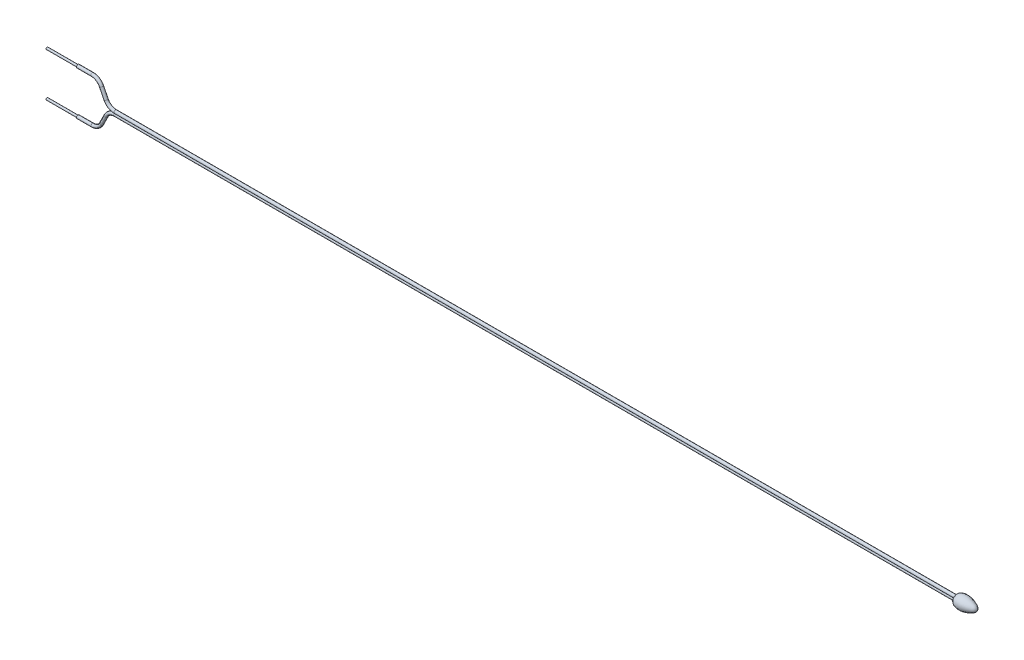
SolidWorks part; units mm, degrees
material "Медь"
ref_plane "Спереди" through (0, 0, 0) normal (0, 0, 1) x (1, 0, 0)
ref_plane "Сверху" through (0, 0, 0) normal (0, 1, 0) x (1, 0, 0)
ref_plane "Справа" through (0, 0, 0) normal (1, 0, 0) x (0, 0, -1)
sketch "Эскиз1" plane through (0, 0, 0) normal (0, 0, 1) x (1, 0, 0)
  line L0 (0, 0) -> (0, 0.3)
  line L1 (0, 0) -> (2.1977, 0) construction
  line L2 (2, 0) -> (0, 0)
  spline S0 degree 3 poles (0, 0.3) (0.1151, 0.5518) (0.7679, 0.6612) (1.4471, 0.471) (1.9856, 0.2262) (2, 0) knots 0 0 0 0 0.344144 0.722891 1 1 1 1
  dimension "D1" = 0.3
  dimension "D2" = 2
  dimension "D3" = 0.6
  dimension "D4" = 0.7
revolve "Повернуть1" add sketch "Эскиз1" angle 360 about L1
sketch "Эскиз2" plane through (0, 0, 0) normal (0, 0, 1) x (1, 0, 0)
  line L0 (0, 0.12) -> (-81.382, 0.12)
  line L1 (0, 0.3) -> (0, -0.3) construction
  line L2 (-82.2764, 0.6728) -> (-82.7236, 1.5672)
  line L3 (-83.618, 2.12) -> (-88, 2.12)
  arc A0 (-82.7236, 1.5672) -> (-83.618, 2.12) centre (-83.618, 1.12) ccw
  arc A1 (-81.382, 0.12) -> (-82.2764, 0.6728) centre (-81.382, 1.12) cw
  point P9 (-83, 2.12)
  point P12 (-82, 0.12)
  dimension "D5" = 1
  dimension "D1" = 5
  dimension "D2" = 1
  dimension "D3" = 88
  dimension "D4" = 2
  dimension "D6" = 0.12
sketch "Эскиз3" plane through (0, 0, 0) normal (-1, 0, 0) x (0, 0, 1)
  circle A0 centre (0, 0.12) radius 0.15
  dimension "D1" = 0.3
sweep "По траектории1" add profiles "Эскиз3" path "Эскиз2"
sketch "Эскиз4" plane through (-88, 0, 0) normal (-1, 0, 0) x (0, 0, 1)
  circle A0 centre (0, 2.12) radius 0.1
  circle A1 centre (0, 2.12) radius 0.2231
  dimension "D1" = 0.2
extrude "Вырез-Вытянуть1" cut sketch "Эскиз4" against normal blind 3
mirror "Зеркальное отражение3" about plane through (0, 0, 0) normal (0, 1, 0) of "Вырез-Вытянуть1", "По траектории1"
